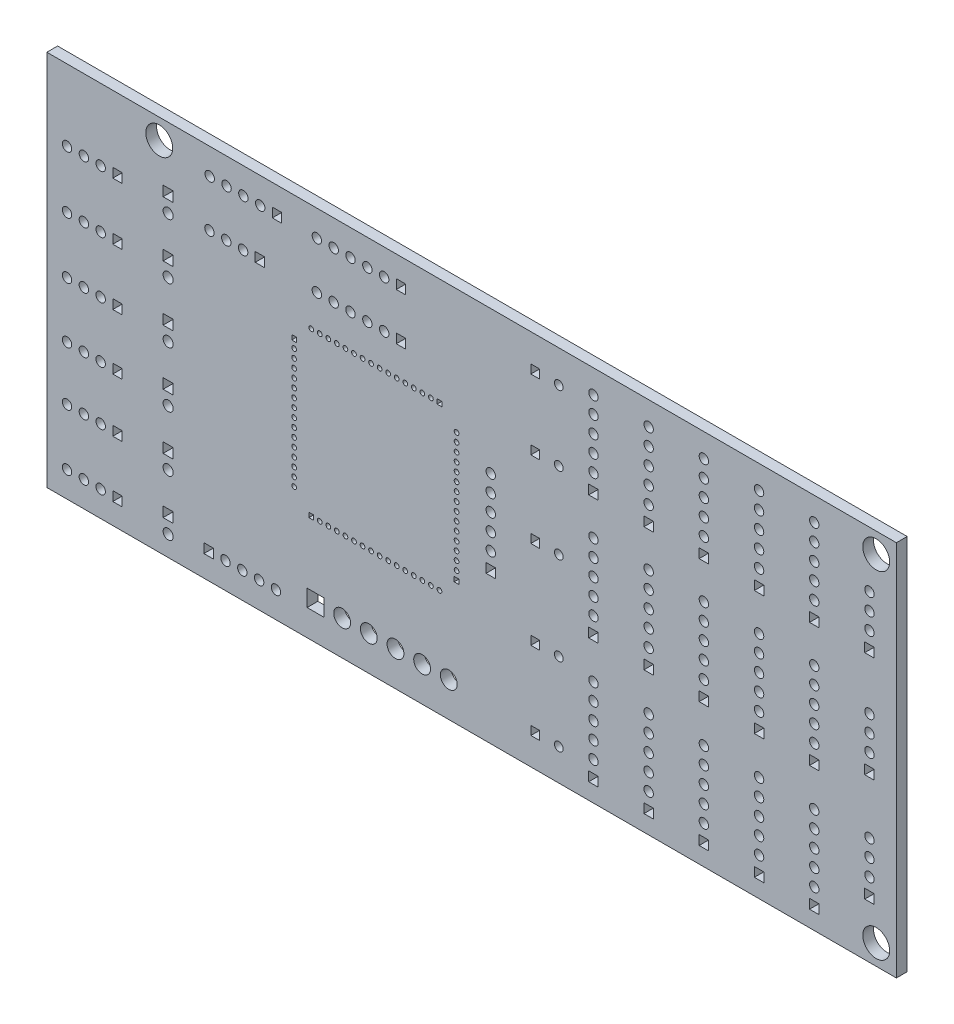
SolidWorks part; units mm, degrees
ref_plane "Front Plane" through (0, 0, 0) normal (0, 0, 1) x (1, 0, 0)
ref_plane "Top Plane" through (0, 0, 0) normal (0, 1, 0) x (1, 0, 0)
ref_plane "Right Plane" through (0, 0, 0) normal (1, 0, 0) x (0, 0, -1)
sketch "Model" plane through (0, 0, 0) normal (0, 0, 1) x (1, 0, 0)
  line L0 (24.96, 3.89) -> (24.96, 6.39)
  line L1 (24.96, 6.39) -> (27.46, 6.39)
  line L2 (27.46, 6.39) -> (27.46, 3.89)
  line L3 (27.46, 3.89) -> (24.96, 3.89)
  line L260 (22.685, 37.875) -> (23.385, 37.875)
  line L261 (23.385, 37.875) -> (23.385, 37.175)
  line L262 (23.385, 37.175) -> (22.685, 37.175)
  line L263 (22.685, 37.175) -> (22.685, 37.875)
  line L264 (25.225, 15.585) -> (25.225, 16.285)
  line L265 (25.225, 16.285) -> (25.925, 16.285)
  line L266 (25.925, 16.285) -> (25.925, 15.585)
  line L267 (25.925, 15.585) -> (25.225, 15.585)
  line L268 (47.515, 18.125) -> (46.815, 18.125)
  line L269 (46.815, 18.125) -> (46.815, 18.825)
  line L270 (46.815, 18.825) -> (47.515, 18.825)
  line L271 (47.515, 18.825) -> (47.515, 18.125)
  line L272 (44.975, 40.415) -> (44.975, 39.715)
  line L273 (44.975, 39.715) -> (44.275, 39.715)
  line L274 (44.275, 39.715) -> (44.275, 40.415)
  line L275 (44.275, 40.415) -> (44.975, 40.415)
  line L276 (3.57, 47.54) -> (5.07, 47.54)
  line L277 (5.07, 47.54) -> (5.07, 46.04)
  line L278 (5.07, 46.04) -> (3.57, 46.04)
  line L279 (3.57, 46.04) -> (3.57, 47.54)
  line L280 (3.57, 39.285) -> (5.07, 39.285)
  line L281 (5.07, 39.285) -> (5.07, 37.785)
  line L282 (5.07, 37.785) -> (3.57, 37.785)
  line L283 (3.57, 37.785) -> (3.57, 39.285)
  line L284 (3.57, 31.03) -> (5.07, 31.03)
  line L285 (5.07, 31.03) -> (5.07, 29.53)
  line L286 (5.07, 29.53) -> (3.57, 29.53)
  line L287 (3.57, 29.53) -> (3.57, 31.03)
  line L288 (3.57, 22.775) -> (5.07, 22.775)
  line L289 (5.07, 22.775) -> (5.07, 21.275)
  line L290 (5.07, 21.275) -> (3.57, 21.275)
  line L291 (3.57, 21.275) -> (3.57, 22.775)
  line L292 (3.57, 14.52) -> (5.07, 14.52)
  line L293 (5.07, 14.52) -> (5.07, 13.02)
  line L294 (5.07, 13.02) -> (3.57, 13.02)
  line L295 (3.57, 13.02) -> (3.57, 14.52)
  line L296 (3.57, 6.265) -> (5.07, 6.265)
  line L297 (5.07, 6.265) -> (5.07, 4.765)
  line L298 (5.07, 4.765) -> (3.57, 4.765)
  line L299 (3.57, 4.765) -> (3.57, 6.265)
  line L516 (92.8, 39.3) -> (91.4, 39.3)
  line L517 (91.4, 39.3) -> (91.4, 40.7)
  line L518 (91.4, 40.7) -> (92.8, 40.7)
  line L519 (92.8, 40.7) -> (92.8, 39.3)
  line L520 (84.6, 39.3) -> (83.2, 39.3)
  line L521 (83.2, 39.3) -> (83.2, 40.7)
  line L522 (83.2, 40.7) -> (84.6, 40.7)
  line L523 (84.6, 40.7) -> (84.6, 39.3)
  line L524 (76.4, 39.3) -> (75, 39.3)
  line L525 (75, 39.3) -> (75, 40.7)
  line L526 (75, 40.7) -> (76.4, 40.7)
  line L527 (76.4, 40.7) -> (76.4, 39.3)
  line L528 (68.2, 39.3) -> (66.8, 39.3)
  line L529 (66.8, 39.3) -> (66.8, 40.7)
  line L530 (66.8, 40.7) -> (68.2, 40.7)
  line L531 (68.2, 40.7) -> (68.2, 39.3)
  line L532 (92.8, 20.9) -> (91.4, 20.9)
  line L533 (91.4, 20.9) -> (91.4, 22.3)
  line L534 (91.4, 22.3) -> (92.8, 22.3)
  line L535 (92.8, 22.3) -> (92.8, 20.9)
  line L536 (84.6, 20.9) -> (83.2, 20.9)
  line L537 (83.2, 20.9) -> (83.2, 22.3)
  line L538 (83.2, 22.3) -> (84.6, 22.3)
  line L539 (84.6, 22.3) -> (84.6, 20.9)
  line L540 (76.4, 20.9) -> (75, 20.9)
  line L541 (75, 20.9) -> (75, 22.3)
  line L542 (75, 22.3) -> (76.4, 22.3)
  line L543 (76.4, 22.3) -> (76.4, 20.9)
  line L544 (68.2, 20.9) -> (66.8, 20.9)
  line L545 (66.8, 20.9) -> (66.8, 22.3)
  line L546 (66.8, 22.3) -> (68.2, 22.3)
  line L547 (68.2, 22.3) -> (68.2, 20.9)
  line L548 (101, 2.4) -> (99.6, 2.4)
  line L549 (99.6, 2.4) -> (99.6, 3.8)
  line L550 (99.6, 3.8) -> (101, 3.8)
  line L551 (101, 3.8) -> (101, 2.4)
  line L552 (92.8, 2.4) -> (91.4, 2.4)
  line L553 (91.4, 2.4) -> (91.4, 3.8)
  line L554 (91.4, 3.8) -> (92.8, 3.8)
  line L555 (92.8, 3.8) -> (92.8, 2.4)
  line L556 (84.6, 2.4) -> (83.2, 2.4)
  line L557 (83.2, 2.4) -> (83.2, 3.8)
  line L558 (83.2, 3.8) -> (84.6, 3.8)
  line L559 (84.6, 3.8) -> (84.6, 2.4)
  line L560 (76.4, 2.4) -> (75, 2.4)
  line L561 (75, 2.4) -> (75, 3.8)
  line L562 (75, 3.8) -> (76.4, 3.8)
  line L563 (76.4, 3.8) -> (76.4, 2.4)
  line L564 (68.2, 2.4) -> (66.8, 2.4)
  line L565 (66.8, 2.4) -> (66.8, 3.8)
  line L566 (66.8, 3.8) -> (68.2, 3.8)
  line L567 (68.2, 3.8) -> (68.2, 2.4)
  line L568 (101, 20.9) -> (99.6, 20.9)
  line L569 (99.6, 20.9) -> (99.6, 22.3)
  line L570 (99.6, 22.3) -> (101, 22.3)
  line L571 (101, 22.3) -> (101, 20.9)
  line L572 (101, 39.3) -> (99.6, 39.3)
  line L573 (99.6, 39.3) -> (99.6, 40.7)
  line L574 (99.6, 40.7) -> (101, 40.7)
  line L575 (101, 40.7) -> (101, 39.3)
  line L576 (39.61, 52.83) -> (39.61, 51.43)
  line L577 (39.61, 51.43) -> (38.21, 51.43)
  line L578 (38.21, 51.43) -> (38.21, 52.83)
  line L579 (38.21, 52.83) -> (39.61, 52.83)
  line L580 (39.61, 45.845) -> (39.61, 44.445)
  line L581 (39.61, 44.445) -> (38.21, 44.445)
  line L582 (38.21, 44.445) -> (38.21, 45.845)
  line L583 (38.21, 45.845) -> (39.61, 45.845)
  line L584 (52.945, 21.585) -> (51.545, 21.585)
  line L585 (51.545, 21.585) -> (51.545, 22.985)
  line L586 (51.545, 22.985) -> (52.945, 22.985)
  line L587 (52.945, 22.985) -> (52.945, 21.585)
  line L1068 (21.195, 52.83) -> (21.195, 51.43)
  line L1069 (21.195, 51.43) -> (19.795, 51.43)
  line L1070 (19.795, 51.43) -> (19.795, 52.83)
  line L1071 (19.795, 52.83) -> (21.195, 52.83)
  line L1072 (9.635, 3.17) -> (9.635, 4.57)
  line L1073 (9.635, 4.57) -> (11.035, 4.57)
  line L1074 (11.035, 4.57) -> (11.035, 3.17)
  line L1075 (11.035, 3.17) -> (9.635, 3.17)
  line L1076 (-2.5, 4.5) -> (-2.5, 3.1)
  line L1077 (-2.5, 3.1) -> (-3.9, 3.1)
  line L1078 (-3.9, 3.1) -> (-3.9, 4.5)
  line L1079 (-3.9, 4.5) -> (-2.5, 4.5)
  line L1080 (-2.5, 12.9) -> (-2.5, 11.5)
  line L1081 (-2.5, 11.5) -> (-3.9, 11.5)
  line L1082 (-3.9, 11.5) -> (-3.9, 12.9)
  line L1083 (-3.9, 12.9) -> (-2.5, 12.9)
  line L1084 (-2.5, 20.9) -> (-2.5, 19.5)
  line L1085 (-2.5, 19.5) -> (-3.9, 19.5)
  line L1086 (-3.9, 19.5) -> (-3.9, 20.9)
  line L1087 (-3.9, 20.9) -> (-2.5, 20.9)
  line L1088 (-2.5, 29.2) -> (-2.5, 27.8)
  line L1089 (-2.5, 27.8) -> (-3.9, 27.8)
  line L1090 (-3.9, 27.8) -> (-3.9, 29.2)
  line L1091 (-3.9, 29.2) -> (-2.5, 29.2)
  line L1092 (-2.5, 37.6) -> (-2.5, 36.2)
  line L1093 (-2.5, 36.2) -> (-3.9, 36.2)
  line L1094 (-3.9, 36.2) -> (-3.9, 37.6)
  line L1095 (-3.9, 37.6) -> (-2.5, 37.6)
  line L1096 (-2.5, 46.1) -> (-2.5, 44.7)
  line L1097 (-2.5, 44.7) -> (-3.9, 44.7)
  line L1098 (-3.9, 44.7) -> (-3.9, 46.1)
  line L1099 (-3.9, 46.1) -> (-2.5, 46.1)
  line L1100 (18.655, 45.845) -> (18.655, 44.445)
  line L1101 (18.655, 44.445) -> (17.255, 44.445)
  line L1102 (17.255, 44.445) -> (17.255, 45.845)
  line L1103 (17.255, 45.845) -> (18.655, 45.845)
  line L1104 (109.2, 39.5) -> (107.8, 39.5)
  line L1105 (107.8, 39.5) -> (107.8, 40.9)
  line L1106 (107.8, 40.9) -> (109.2, 40.9)
  line L1107 (109.2, 40.9) -> (109.2, 39.5)
  line L1108 (109.2, 23.8) -> (107.8, 23.8)
  line L1109 (107.8, 23.8) -> (107.8, 25.2)
  line L1110 (107.8, 25.2) -> (109.2, 25.2)
  line L1111 (109.2, 25.2) -> (109.2, 23.8)
  line L1112 (109.2, 7.8) -> (107.8, 7.8)
  line L1113 (107.8, 7.8) -> (107.8, 9.2)
  line L1114 (107.8, 9.2) -> (109.2, 9.2)
  line L1115 (109.2, 9.2) -> (109.2, 7.8)
  line L1116 (58.2, 4.05) -> (58.2, 5.35)
  line L1117 (58.2, 5.35) -> (59.5, 5.35)
  line L1118 (59.5, 5.35) -> (59.5, 4.05)
  line L1119 (59.5, 4.05) -> (58.2, 4.05)
  line L1120 (58.2, 15.65) -> (58.2, 16.95)
  line L1121 (58.2, 16.95) -> (59.5, 16.95)
  line L1122 (59.5, 16.95) -> (59.5, 15.65)
  line L1123 (59.5, 15.65) -> (58.2, 15.65)
  line L1124 (58.2, 28.75) -> (58.2, 30.05)
  line L1125 (58.2, 30.05) -> (59.5, 30.05)
  line L1126 (59.5, 30.05) -> (59.5, 28.75)
  line L1127 (59.5, 28.75) -> (58.2, 28.75)
  line L1128 (58.2, 50.55) -> (58.2, 51.85)
  line L1129 (58.2, 51.85) -> (59.5, 51.85)
  line L1130 (59.5, 51.85) -> (59.5, 50.55)
  line L1131 (59.5, 50.55) -> (58.2, 50.55)
  line L1132 (58.2, 40.15) -> (58.2, 41.45)
  line L1133 (58.2, 41.45) -> (59.5, 41.45)
  line L1134 (59.5, 41.45) -> (59.5, 40.15)
  line L1135 (59.5, 40.15) -> (58.2, 40.15)
  line L1136 (0, 0) -> (106, 0)
  line L1137 (106, 0) -> (112.5, 0)
  line L1138 (112.5, 0) -> (112.5, 56)
  line L1139 (112.5, 56) -> (106, 56)
  line L1140 (106, 56) -> (0, 56)
  line L1141 (0, 56) -> (-13.7, 56)
  line L1142 (-13.7, 56) -> (-13.7, 0)
  line L1143 (-13.7, 0) -> (0, 0)
  circle A0 centre (30.17, 5.14) radius 1.25
  circle A1 centre (34.13, 5.14) radius 1.25
  circle A2 centre (38.09, 5.14) radius 1.25
  circle A3 centre (42.05, 5.14) radius 1.25
  circle A4 centre (46.01, 5.14) radius 1.25
  circle A5 centre (23.035, 36.255) radius 0.35
  circle A6 centre (23.035, 34.985) radius 0.35
  circle A7 centre (23.035, 33.715) radius 0.35
  circle A8 centre (23.035, 32.445) radius 0.35
  circle A9 centre (23.035, 31.175) radius 0.35
  circle A10 centre (23.035, 29.905) radius 0.35
  circle A11 centre (23.035, 28.635) radius 0.35
  circle A12 centre (23.035, 27.365) radius 0.35
  circle A13 centre (23.035, 26.095) radius 0.35
  circle A14 centre (23.035, 24.825) radius 0.35
  circle A15 centre (23.035, 23.555) radius 0.35
  circle A16 centre (23.035, 22.285) radius 0.35
  circle A17 centre (23.035, 21.015) radius 0.35
  circle A18 centre (23.035, 19.745) radius 0.35
  circle A19 centre (23.035, 18.475) radius 0.35
  circle A20 centre (26.845, 15.935) radius 0.35
  circle A21 centre (28.115, 15.935) radius 0.35
  circle A22 centre (29.385, 15.935) radius 0.35
  circle A23 centre (30.655, 15.935) radius 0.35
  circle A24 centre (31.925, 15.935) radius 0.35
  circle A25 centre (33.195, 15.935) radius 0.35
  circle A26 centre (34.465, 15.935) radius 0.35
  circle A27 centre (35.735, 15.935) radius 0.35
  circle A28 centre (37.005, 15.935) radius 0.35
  circle A29 centre (38.275, 15.935) radius 0.35
  circle A30 centre (39.545, 15.935) radius 0.35
  circle A31 centre (40.815, 15.935) radius 0.35
  circle A32 centre (42.085, 15.935) radius 0.35
  circle A33 centre (43.355, 15.935) radius 0.35
  circle A34 centre (44.625, 15.935) radius 0.35
  circle A35 centre (47.165, 19.745) radius 0.35
  circle A36 centre (47.165, 21.015) radius 0.35
  circle A37 centre (47.165, 22.285) radius 0.35
  circle A38 centre (47.165, 23.555) radius 0.35
  circle A39 centre (47.165, 24.825) radius 0.35
  circle A40 centre (47.165, 26.095) radius 0.35
  circle A41 centre (47.165, 27.365) radius 0.35
  circle A42 centre (47.165, 28.635) radius 0.35
  circle A43 centre (47.165, 29.905) radius 0.35
  circle A44 centre (47.165, 31.175) radius 0.35
  circle A45 centre (47.165, 32.445) radius 0.35
  circle A46 centre (47.165, 33.715) radius 0.35
  circle A47 centre (47.165, 34.985) radius 0.35
  circle A48 centre (47.165, 36.255) radius 0.35
  circle A49 centre (47.165, 37.525) radius 0.35
  circle A50 centre (43.355, 40.065) radius 0.35
  circle A51 centre (42.085, 40.065) radius 0.35
  circle A52 centre (40.815, 40.065) radius 0.35
  circle A53 centre (39.545, 40.065) radius 0.35
  circle A54 centre (38.275, 40.065) radius 0.35
  circle A55 centre (37.005, 40.065) radius 0.35
  circle A56 centre (35.735, 40.065) radius 0.35
  circle A57 centre (34.465, 40.065) radius 0.35
  circle A58 centre (33.195, 40.065) radius 0.35
  circle A59 centre (31.925, 40.065) radius 0.35
  circle A60 centre (30.655, 40.065) radius 0.35
  circle A61 centre (29.385, 40.065) radius 0.35
  circle A62 centre (28.115, 40.065) radius 0.35
  circle A63 centre (26.845, 40.065) radius 0.35
  circle A64 centre (25.575, 40.065) radius 0.35
  circle A65 centre (4.32, 44.29) radius 0.75
  circle A66 centre (4.32, 36.035) radius 0.75
  circle A67 centre (4.32, 27.78) radius 0.75
  circle A68 centre (4.32, 19.525) radius 0.75
  circle A69 centre (4.32, 11.27) radius 0.75
  circle A70 centre (4.32, 3.015) radius 0.75
  circle A71 centre (92.1, 42.5) radius 0.7
  circle A72 centre (92.1, 45) radius 0.7
  circle A73 centre (92.1, 47.5) radius 0.7
  circle A74 centre (92.1, 50) radius 0.7
  circle A75 centre (92.1, 52.5) radius 0.7
  circle A76 centre (83.9, 42.5) radius 0.7
  circle A77 centre (83.9, 45) radius 0.7
  circle A78 centre (83.9, 47.5) radius 0.7
  circle A79 centre (83.9, 50) radius 0.7
  circle A80 centre (83.9, 52.5) radius 0.7
  circle A81 centre (75.7, 42.5) radius 0.7
  circle A82 centre (75.7, 45) radius 0.7
  circle A83 centre (75.7, 47.5) radius 0.7
  circle A84 centre (75.7, 50) radius 0.7
  circle A85 centre (75.7, 52.5) radius 0.7
  circle A86 centre (67.5, 42.5) radius 0.7
  circle A87 centre (67.5, 45) radius 0.7
  circle A88 centre (67.5, 47.5) radius 0.7
  circle A89 centre (67.5, 50) radius 0.7
  circle A90 centre (67.5, 52.5) radius 0.7
  circle A91 centre (92.1, 24.1) radius 0.7
  circle A92 centre (92.1, 26.6) radius 0.7
  circle A93 centre (92.1, 29.1) radius 0.7
  circle A94 centre (92.1, 31.6) radius 0.7
  circle A95 centre (92.1, 34.1) radius 0.7
  circle A96 centre (83.9, 24.1) radius 0.7
  circle A97 centre (83.9, 26.6) radius 0.7
  circle A98 centre (83.9, 29.1) radius 0.7
  circle A99 centre (83.9, 31.6) radius 0.7
  circle A100 centre (83.9, 34.1) radius 0.7
  circle A101 centre (75.7, 24.1) radius 0.7
  circle A102 centre (75.7, 26.6) radius 0.7
  circle A103 centre (75.7, 29.1) radius 0.7
  circle A104 centre (75.7, 31.6) radius 0.7
  circle A105 centre (75.7, 34.1) radius 0.7
  circle A106 centre (67.5, 24.1) radius 0.7
  circle A107 centre (67.5, 26.6) radius 0.7
  circle A108 centre (67.5, 29.1) radius 0.7
  circle A109 centre (67.5, 31.6) radius 0.7
  circle A110 centre (67.5, 34.1) radius 0.7
  circle A111 centre (100.3, 5.6) radius 0.7
  circle A112 centre (100.3, 8.1) radius 0.7
  circle A113 centre (100.3, 10.6) radius 0.7
  circle A114 centre (100.3, 13.1) radius 0.7
  circle A115 centre (100.3, 15.6) radius 0.7
  circle A116 centre (92.1, 5.6) radius 0.7
  circle A117 centre (92.1, 8.1) radius 0.7
  circle A118 centre (92.1, 10.6) radius 0.7
  circle A119 centre (92.1, 13.1) radius 0.7
  circle A120 centre (92.1, 15.6) radius 0.7
  circle A121 centre (83.9, 5.6) radius 0.7
  circle A122 centre (83.9, 8.1) radius 0.7
  circle A123 centre (83.9, 10.6) radius 0.7
  circle A124 centre (83.9, 13.1) radius 0.7
  circle A125 centre (83.9, 15.6) radius 0.7
  circle A126 centre (75.7, 5.6) radius 0.7
  circle A127 centre (75.7, 8.1) radius 0.7
  circle A128 centre (75.7, 10.6) radius 0.7
  circle A129 centre (75.7, 13.1) radius 0.7
  circle A130 centre (75.7, 15.6) radius 0.7
  circle A131 centre (67.5, 5.6) radius 0.7
  circle A132 centre (67.5, 8.1) radius 0.7
  circle A133 centre (67.5, 10.6) radius 0.7
  circle A134 centre (67.5, 13.1) radius 0.7
  circle A135 centre (67.5, 15.6) radius 0.7
  circle A136 centre (100.3, 24.1) radius 0.7
  circle A137 centre (100.3, 26.6) radius 0.7
  circle A138 centre (100.3, 29.1) radius 0.7
  circle A139 centre (100.3, 31.6) radius 0.7
  circle A140 centre (100.3, 34.1) radius 0.7
  circle A141 centre (100.3, 42.5) radius 0.7
  circle A142 centre (100.3, 45) radius 0.7
  circle A143 centre (100.3, 47.5) radius 0.7
  circle A144 centre (100.3, 50) radius 0.7
  circle A145 centre (100.3, 52.5) radius 0.7
  circle A146 centre (36.41, 52.13) radius 0.7
  circle A147 centre (33.91, 52.13) radius 0.7
  circle A148 centre (31.41, 52.13) radius 0.7
  circle A149 centre (28.91, 52.13) radius 0.7
  circle A150 centre (26.41, 52.13) radius 0.7
  circle A151 centre (36.41, 45.145) radius 0.7
  circle A152 centre (33.91, 45.145) radius 0.7
  circle A153 centre (31.41, 45.145) radius 0.7
  circle A154 centre (28.91, 45.145) radius 0.7
  circle A155 centre (26.41, 45.145) radius 0.7
  circle A156 centre (52.245, 24.785) radius 0.7
  circle A157 centre (52.245, 27.285) radius 0.7
  circle A158 centre (52.245, 29.785) radius 0.7
  circle A159 centre (52.245, 32.285) radius 0.7
  circle A160 centre (52.245, 34.785) radius 0.7
  circle A161 centre (17.995, 52.13) radius 0.7
  circle A162 centre (15.495, 52.13) radius 0.7
  circle A163 centre (12.995, 52.13) radius 0.7
  circle A164 centre (10.495, 52.13) radius 0.7
  circle A165 centre (12.835, 3.87) radius 0.7
  circle A166 centre (15.335, 3.87) radius 0.7
  circle A167 centre (17.835, 3.87) radius 0.7
  circle A168 centre (20.335, 3.87) radius 0.7
  circle A169 centre (-5.7, 3.8) radius 0.7
  circle A170 centre (-8.2, 3.8) radius 0.7
  circle A171 centre (-10.7, 3.8) radius 0.7
  circle A172 centre (-5.7, 12.2) radius 0.7
  circle A173 centre (-8.2, 12.2) radius 0.7
  circle A174 centre (-10.7, 12.2) radius 0.7
  circle A175 centre (-5.7, 20.2) radius 0.7
  circle A176 centre (-8.2, 20.2) radius 0.7
  circle A177 centre (-10.7, 20.2) radius 0.7
  circle A178 centre (-5.7, 28.5) radius 0.7
  circle A179 centre (-8.2, 28.5) radius 0.7
  circle A180 centre (-10.7, 28.5) radius 0.7
  circle A181 centre (-5.7, 36.9) radius 0.7
  circle A182 centre (-8.2, 36.9) radius 0.7
  circle A183 centre (-10.7, 36.9) radius 0.7
  circle A184 centre (-5.7, 45.4) radius 0.7
  circle A185 centre (-8.2, 45.4) radius 0.7
  circle A186 centre (-10.7, 45.4) radius 0.7
  circle A187 centre (15.455, 45.145) radius 0.7
  circle A188 centre (12.955, 45.145) radius 0.7
  circle A189 centre (10.455, 45.145) radius 0.7
  circle A190 centre (108.5, 42.7) radius 0.7
  circle A191 centre (108.5, 45.2) radius 0.7
  circle A192 centre (108.5, 47.7) radius 0.7
  circle A193 centre (108.5, 27) radius 0.7
  circle A194 centre (108.5, 29.5) radius 0.7
  circle A195 centre (108.5, 32) radius 0.7
  circle A196 centre (108.5, 11) radius 0.7
  circle A197 centre (108.5, 13.5) radius 0.7
  circle A198 centre (108.5, 16) radius 0.7
  circle A199 centre (62.35, 4.7) radius 0.65
  circle A200 centre (62.35, 16.3) radius 0.65
  circle A201 centre (62.35, 29.4) radius 0.65
  circle A202 centre (62.35, 51.2) radius 0.65
  circle A203 centre (62.35, 40.8) radius 0.65
  circle A204 centre (3, 53) radius 2
  circle A205 centre (109.5, 3) radius 2
  circle A206 centre (109.5, 53) radius 2
extrude "Boss-Extrude1" add sketch "Model" along normal blind 1.6
